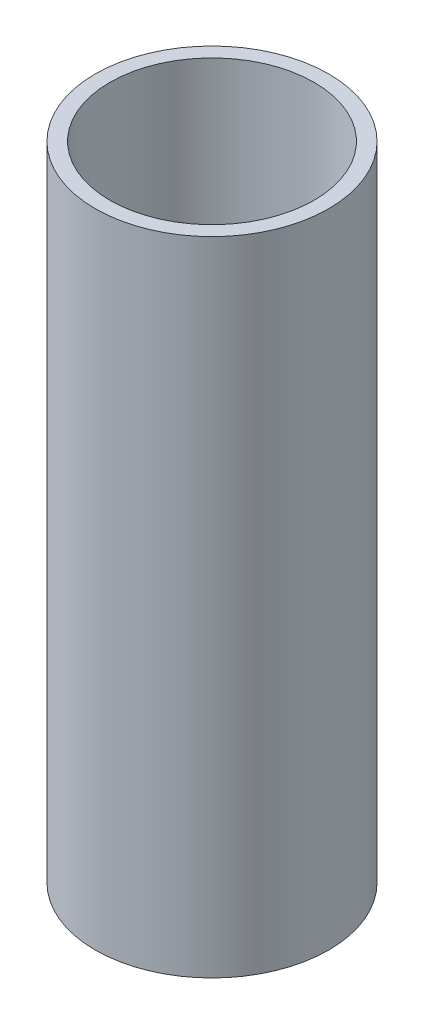
SolidWorks part; units mm, degrees
ref_plane "Plan de face" through (0, 0, 0) normal (0, 0, 1) x (1, 0, 0)
ref_plane "Plan de dessus" through (0, 0, 0) normal (0, 1, 0) x (1, 0, 0)
ref_plane "Plan de droite" through (0, 0, 0) normal (1, 0, 0) x (0, 0, -1)
sketch "Esquisse2" plane through (0, 0, 0) normal (0, 1, 0) x (1, 0, 0)
  circle A0 centre (0, 0) radius 17.5
  circle A1 centre (0, 0) radius 20
  dimension "D1" = 35
  dimension "D2" = 40
extrude "Boss.-Extru.2" add sketch "Esquisse2" along normal blind 105
sketch "Esquisse3" plane through (0, 0, 0) normal (0, -1, 0) x (-1, 0, 0)
  circle A0 centre (0, 0) radius 20
extrude "Boss.-Extru.3" add sketch "Esquisse3" along normal blind 5
